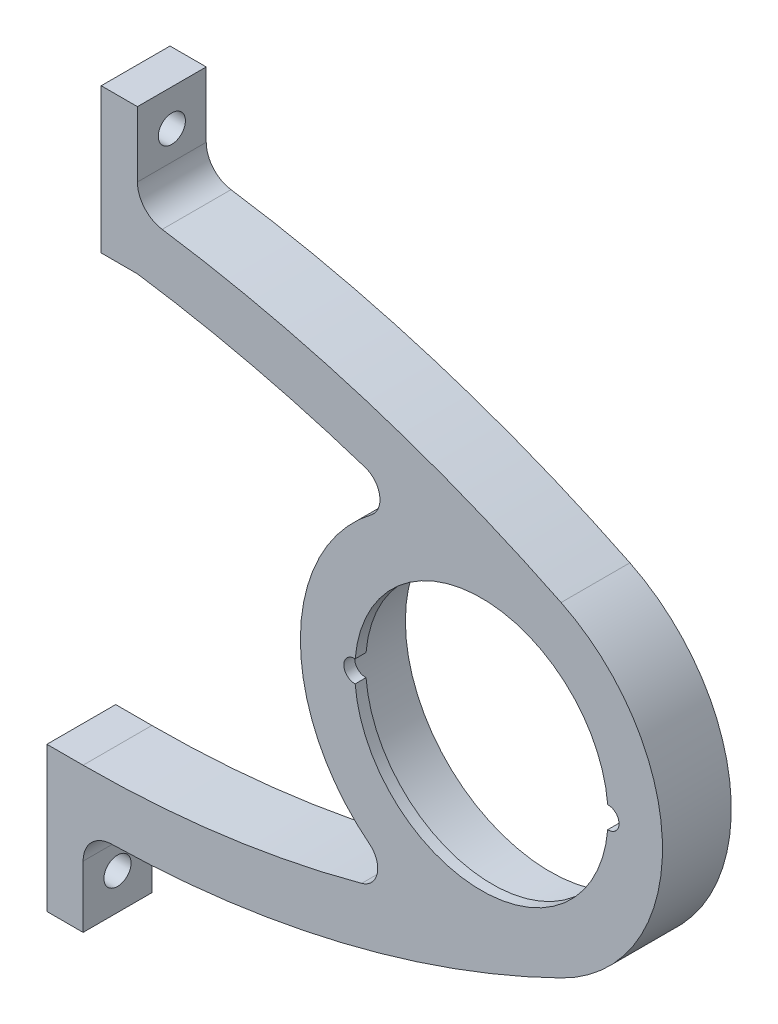
SolidWorks part; units mm, degrees
material "6061 Alloy"
ref_plane "Front Plane" through (0, 0, 0) normal (0, 0, 1) x (1, 0, 0)
ref_plane "Top Plane" through (0, 0, 0) normal (0, 1, 0) x (1, 0, 0)
ref_plane "Right Plane" through (0, 0, 0) normal (1, 0, 0) x (0, 0, -1)
sketch "Sketch1" plane through (0, 0, 0) normal (0, 0, 1) x (1, 0, 0)
  line L0 (-133.35, 133.35) -> (-133.35, 82.55)
  line L1 (-133.35, 82.55) -> (-120.65, 82.55)
  line L2 (-133.35, 133.35) -> (-120.65, 133.35)
  line L3 (-120.65, 133.35) -> (-120.65, 101.6)
  line L5 (-152.4, -76.2) -> (-139.7, -76.2)
  line L6 (-152.4, -76.2) -> (-152.4, -127)
  line L7 (-152.4, -127) -> (-139.7, -127)
  line L8 (-139.7, -127) -> (-139.7, -95.25)
  circle A1 centre (0, 0) radius 50.8
  arc A7 (27.94, -57.0229) -> (27.94, 57.0229) centre (0, 0) ccw
  arc A13 (-139.7, -95.25) -> (27.94, -57.0229) centre (-136.9997, 279.6033) ccw
  arc A14 (-25.2005, 58.2854) -> (-25.2005, -58.2854) centre (0, 0) ccw
  arc A15 (-25.2005, -58.2854) -> (-139.7, -76.2) centre (-139.7, 298.6631) cw
  arc A24 (27.94, 57.0229) -> (-120.65, 101.6) centre (-180.9225, -369.2454) ccw
  arc A25 (-25.2005, 58.2854) -> (-120.65, 82.55) centre (-189.2468, -387.1549) ccw
  point P15 (0, 0)
  point P20 (0, 0)
  point P21 (-47.9659, 41.6116)
  point P24 (-56.3434, 29.2859)
  point P26 (26.3507, 57.7745)
  point P27 (-25.2005, 57.7745)
  point P28 (27.94, 57.3429)
  point P29 (-25.2005, 57.0326)
  point P30 (0, 0)
  point P31 (0, 0)
  dimension "D2" = 101.6
  dimension "D25" = 12.7
  dimension "D3" = 50.8
  dimension "D4" = 12.7
  dimension "D5" = 31.75
  dimension "D6" = 133.35
  dimension "D7" = 152.4
  dimension "D8" = 12.7
  dimension "D9" = 50.8
  dimension "D10" = 31.75
  dimension "D11" = 133.35
  dimension "D12" = 127
  dimension "D19" = 167.64
extrude "Boss-Extrude1" add sketch "Sketch1" along normal blind 24.13 contours A1
fillet "Fillet1" radius 10.16 2 edges at (-139.7, -95.25, 12.065) (-120.65, 101.6, 12.065)
fillet "Fillet3" radius 7.62 2 edges at (-25.2005, -58.2854, 12.065) (-25.2005, 58.2854, 12.065)
sketch "Sketch2" plane through (-152.4, 0, 0) normal (-1, 0, 0) x (0, 0, 1)
  line L0 (24.13, 133.35) -> (0, 133.35) construction
  line L1 (24.13, -127) -> (0, -127) construction
  circle A0 centre (12.065, -114.3) radius 4.7625
  circle A1 centre (12.065, 120.65) radius 4.7625
  point P6 (12.065, 133.35)
  dimension "D1" = 9.525
  dimension "D2" = 12.7
  dimension "D3" = 12.7
extrude "Cut-Extrude1" cut sketch "Sketch2" against normal through all
sketch "Sketch3" plane through (0, 0, 24.13) normal (0, 0, 1) x (1, 0, 0)
  circle A0 centre (0, 0) radius 50.8 construction
  circle A1 centre (0, 0) radius 50.8
  arc A2 (-44.2867, -3.8065) -> (44.2867, -3.8065) centre (0, 0) ccw
  arc A3 (-44.2867, 3.8065) -> (-44.2867, -3.8065) centre (-44.45, 0) ccw
  arc A4 (44.2867, -3.8065) -> (44.2867, 3.8065) centre (44.45, 0) ccw
  arc A5 (44.2867, 3.8065) -> (-44.2867, 3.8065) centre (0, 0) ccw
  dimension "D1" = 88.9
  dimension "D2" = 2.54
  dimension "D3" = 2.54
extrude "Boss-Extrude2" add sketch "Sketch3" against normal blind 3.81
